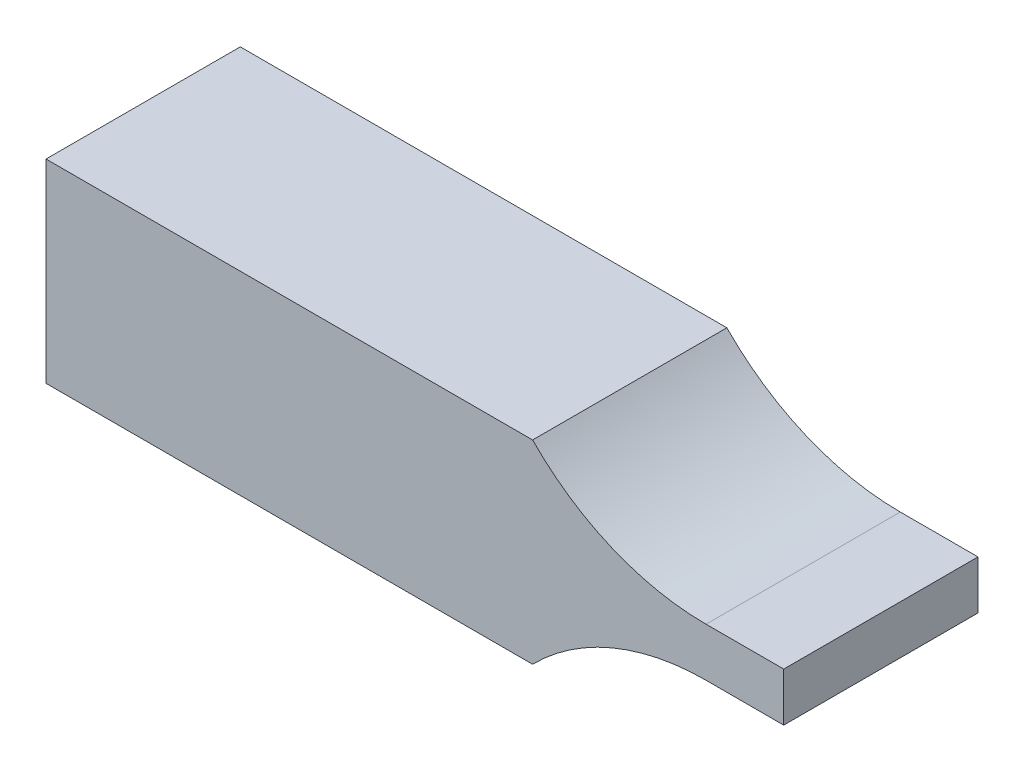
SolidWorks part; units mm, degrees
ref_plane "Front Plane" through (0, 0, 0) normal (0, 0, 1) x (1, 0, 0)
ref_plane "Top Plane" through (0, 0, 0) normal (0, 1, 0) x (1, 0, 0)
ref_plane "Right Plane" through (0, 0, 0) normal (1, 0, 0) x (0, 0, -1)
sketch "Sketch1" plane through (0, 0, 0) normal (0, 0, 1) x (1, 0, 0)
  line L0 (4.4641, -6.5499) -> (-45.6307, -6.5499)
  line L1 (-45.6307, -6.5499) -> (-45.6307, -26.5499)
  line L2 (-45.6307, -26.5499) -> (4.4641, -26.5499)
  line L3 (22.3177, -14.0499) -> (30.3177, -14.0499)
  line L4 (30.3177, -14.0499) -> (30.3177, -19.0499)
  line L5 (30.3177, -19.0499) -> (22.3177, -19.0499)
  arc A0 (4.4641, -6.5499) -> (22.3177, -14.0499) centre (22.3177, 10.9501) ccw
  arc A1 (4.4641, -26.5499) -> (22.3177, -19.0499) centre (22.3177, -44.0499) cw
  circle A2 centre (22.3177, 10.9501) radius 25 construction
  circle A3 centre (22.3177, -44.0499) radius 25 construction
  dimension "D1" = 5
  dimension "D2" = 20
extrude "Boss-Extrude1" add sketch "Sketch1" along normal mid plane 20
